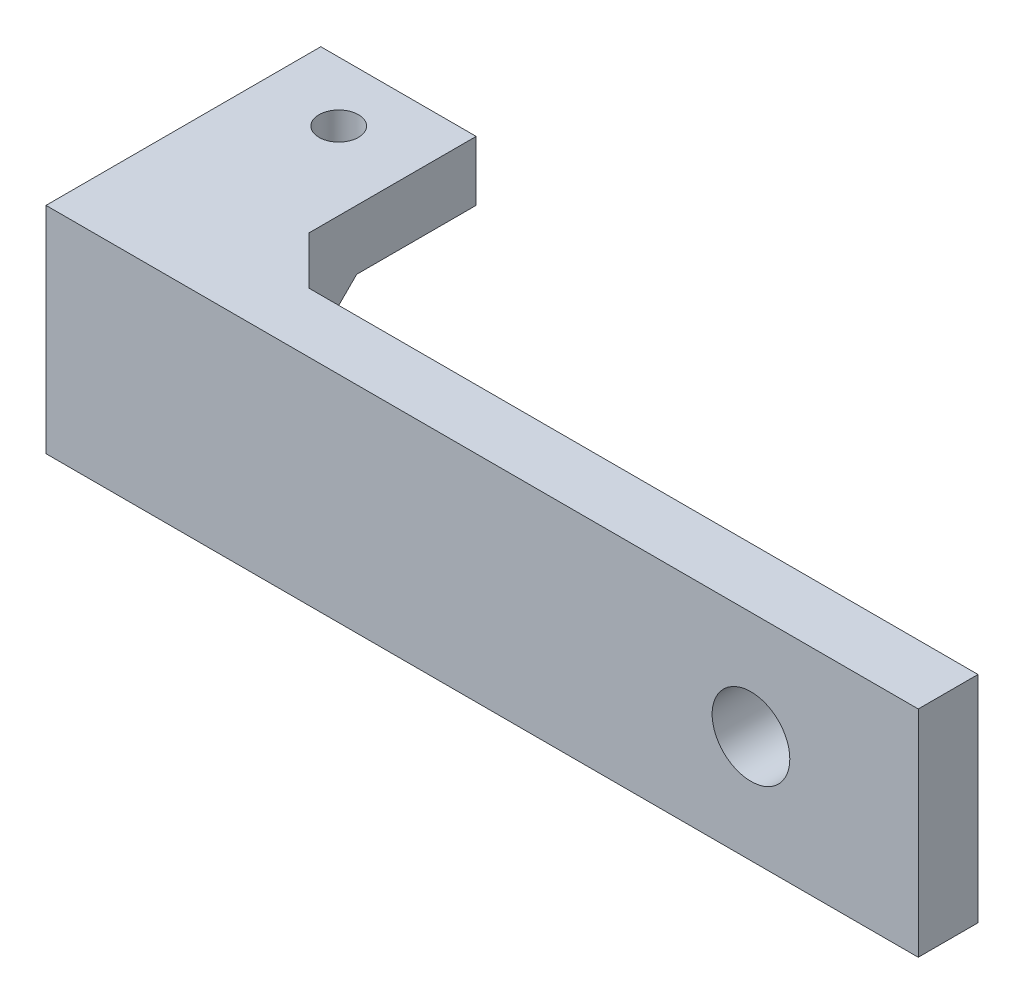
SolidWorks part; units mm, degrees
ref_plane "Ön Düzlem" through (0, 0, 0) normal (0, 0, 1) x (1, 0, 0)
ref_plane "Üst Düzlem" through (0, 0, 0) normal (0, 1, 0) x (1, 0, 0)
ref_plane "Sağ Düzlem" through (0, 0, 0) normal (1, 0, 0) x (0, 0, -1)
sketch "Çizim1" plane through (0, 0, 0) normal (0, 0, 1) x (1, 0, 0)
  line L0 (0, 0) -> (0, 3.6986)
  line L1 (0, 19.8493) -> (-60, 19.8493)
  line L2 (-60, 19.8493) -> (-60, 1.8493)
  line L3 (-60, 1.8493) -> (0, 1.8493)
  line L4 (0, 1.8493) -> (0, 19.8493)
  circle A0 centre (-14, 10.8493) radius 3.25
  dimension "D3" = 14
  dimension "D1" = 60
  dimension "D2" = 18
extrude "Yükseklik-Ekstrüzyon1" add sketch "Çizim1" along normal blind 5 contours L0 L4 L1 L2 L3 A0
sketch "Çizim2" plane through (0, 0, 0) normal (0, 0, -1) x (-1, 0, 0)
  line L0 (60, 19.8493) -> (73, 19.8493)
  line L1 (73, 19.8493) -> (73, 1.8493)
  line L2 (73, 1.8493) -> (60, 1.8493)
  line L3 (60, 19.8493) -> (60, 1.8493)
extrude "Yükseklik-Ekstrüzyon2" add sketch "Çizim2" along normal blind 5 and the other way up to surface (5 mm away) other way up to face at (-10.75, 10.8493, 5)
sketch "Çizim3" plane through (-73, 0, 0) normal (-1, 0, 0) x (0, 0, 1)
  line L0 (-5, 19.8493) -> (-18, 19.8493)
  line L1 (-18, 19.8493) -> (-18, 14.8493)
  line L2 (-18, 14.8493) -> (-5, 14.8493)
  line L3 (-5, 1.8493) -> (-5, 19.8493) construction
  line L4 (-5, 19.8493) -> (-5, 14.8493)
  dimension "D1" = 13
extrude "Yükseklik-Ekstrüzyon3" add sketch "Çizim3" against normal up to surface (13 mm away) up to face at (-60, 10.8493, -2.5)
chamfer "Pah1" distance 3 angle 45 1 edges at (-66.5, 14.8493, -5)
chamfer "Pah2" distance 4 angle 45 1 edges at (-60, 10.8493, 0)
sketch "Çizim4" plane through (-73, 0, 0) normal (-1, 0, 0) x (0, 0, 1)
  line L0 (-5, 11.8493) -> (0, 1.8493)
  line L1 (5, 1.8493) -> (-5, 1.8493) construction
  line L2 (-5, 11.8493) -> (-5, 1.8493)
  line L3 (-5, 1.8493) -> (0, 1.8493)
extrude "Kes-Ekstrüzyon1" cut sketch "Çizim4" against normal blind 23
sketch "Çizim5" plane through (0, 14.8493, 0) normal (0, -1, 0) x (1, 0, 0)
  circle A0 centre (-66.5, -13) radius 1.65
extrude "Kes-Ekstrüzyon2" cut sketch "Çizim5" against normal blind 10
